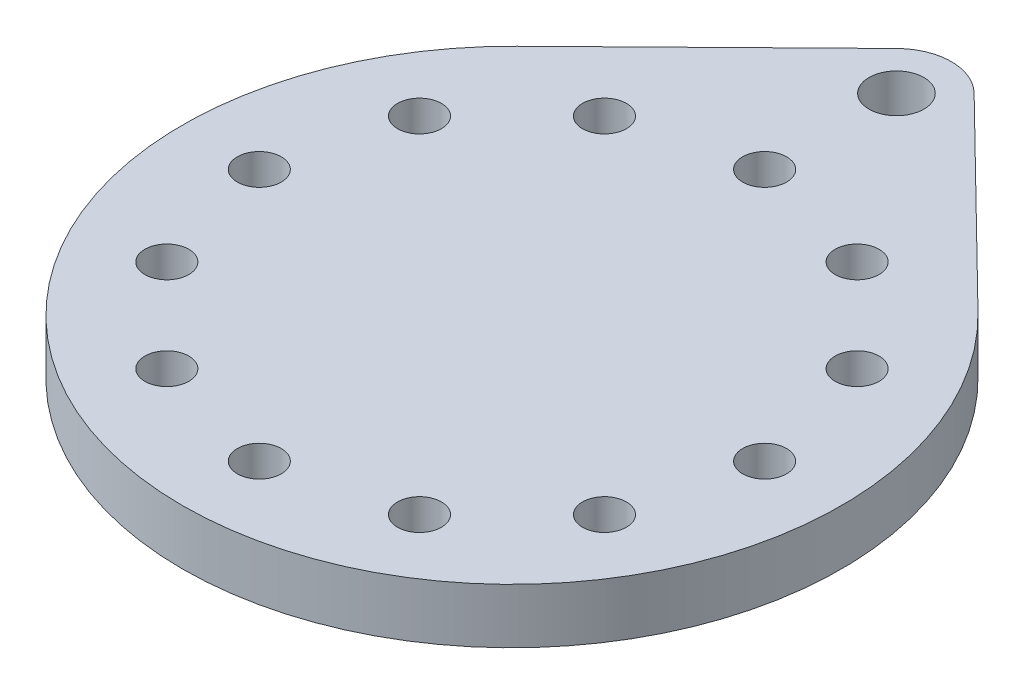
SolidWorks part; units mm, degrees
ref_plane "Front Plane" through (0, 0, 0) normal (0, 0, 1) x (1, 0, 0)
ref_plane "Top Plane" through (0, 0, 0) normal (0, 1, 0) x (1, 0, 0)
ref_plane "Right Plane" through (0, 0, 0) normal (1, 0, 0) x (0, 0, -1)
sketch "Sketch1" plane through (0, 0, 0) normal (0, 1, 0) x (1, 0, 0)
  line L0 (0, 35) -> (0, 0) construction
  line L1 (-3.4993, 38.5714) -> (-20.9956, 21.4286)
  line L2 (3.4993, 38.5714) -> (20.9956, 21.4286)
  circle A0 centre (0, 0) radius 30
  circle A1 centre (0, 0) radius 23 construction
  circle A2 centre (0, 35) radius 2.5
  circle A3 centre (0, 35) radius 5
  circle A4 centre (0, 23) radius 2
  circle A5 centre (11.5, 19.9186) radius 2
  circle A6 centre (19.9186, 11.5) radius 2
  circle A7 centre (23, 0) radius 2
  circle A8 centre (19.9186, -11.5) radius 2
  circle A9 centre (11.5, -19.9186) radius 2
  circle A10 centre (0, -23) radius 2
  circle A11 centre (-11.5, -19.9186) radius 2
  circle A12 centre (-19.9186, -11.5) radius 2
  circle A13 centre (-23, 0) radius 2
  circle A14 centre (-19.9186, 11.5) radius 2
  circle A15 centre (-11.5, 19.9186) radius 2
  point P38 (0, 0)
  dimension "D1" = 60
  dimension "D2" = 46
  dimension "D4" = 5
  dimension "D5" = 4
  dimension "D3" = 35
  dimension "D6" = 12
extrude "Boss-Extrude1" add sketch "Sketch1" along normal blind 5 contours A0 A15 A14 A13 A12 A11 A10 A9 A8 A7 A6 A5 A4 | A3 A0 L2 | A3 L1 A0 | A3 A2
